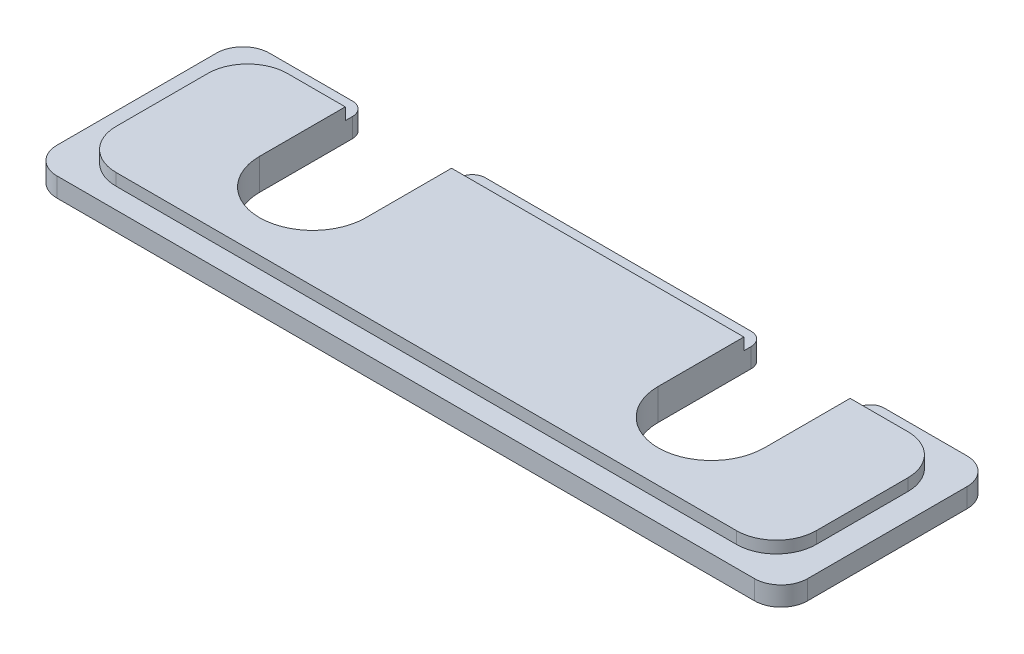
SolidWorks part; units mm, degrees
ref_plane "Front Plane" through (0, 0, 0) normal (0, 0, 1) x (1, 0, 0)
ref_plane "Top Plane" through (0, 0, 0) normal (0, 1, 0) x (1, 0, 0)
ref_plane "Right Plane" through (0, 0, 0) normal (1, 0, 0) x (0, 0, -1)
sketch "Sketch1" plane through (0, 0, 0) normal (0, 1, 0) x (1, 0, 0)
  line L1 (-26.25, -8) -> (26.25, -8)
  line L2 (-28.25, -6) -> (-28.25, 6)
  line L3 (-26.25, 8) -> (26.25, 8)
  line L4 (28.25, -6) -> (28.25, 6)
  line L5 (-28.25, -8) -> (28.25, 8) construction
  line L6 (-28.25, 8) -> (28.25, -8) construction
  arc A0 (26.25, 8) -> (28.25, 6) centre (26.25, 6) cw
  arc A1 (26.25, -8) -> (28.25, -6) centre (26.25, -6) ccw
  arc A2 (-26.25, -8) -> (-28.25, -6) centre (-26.25, -6) cw
  arc A3 (-28.25, 6) -> (-26.25, 8) centre (-26.25, 6) cw
  point P0 (0, 0)
  dimension "D3" = 2
  dimension "D1" = 56.5
  dimension "D2" = 16
extrude "Boss-Extrude1" add sketch "Sketch1" along normal blind 1.45
sketch "Sketch2" plane through (0, 1.45, 0) normal (0, 1, 0) x (1, 0, 0)
  line L1 (-23.35, -6.45) -> (23.35, -6.45)
  line L2 (-26.35, -3.45) -> (-26.35, 3.45)
  line L3 (-23.35, 6.45) -> (23.35, 6.45)
  line L4 (26.35, -3.45) -> (26.35, 3.45)
  line L5 (-26.35, -6.45) -> (26.35, 6.45) construction
  line L6 (-26.35, 6.45) -> (26.35, -6.45) construction
  arc A0 (23.35, -6.45) -> (26.35, -3.45) centre (23.35, -3.45) ccw
  arc A1 (23.35, 6.45) -> (26.35, 3.45) centre (23.35, 3.45) cw
  arc A2 (-23.35, -6.45) -> (-26.35, -3.45) centre (-23.35, -3.45) cw
  arc A3 (-26.35, 3.45) -> (-23.35, 6.45) centre (-23.35, 3.45) cw
  point P0 (0, 0)
  dimension "D3" = 3
  dimension "D1" = 52.7
  dimension "D2" = 12.9
extrude "Boss-Extrude2" add sketch "Sketch2" along normal blind 0.9
sketch "Sketch3" plane through (0, 2.35, 0) normal (0, 1, 0) x (1, 0, 0)
  line L0 (-19, 0) -> (-19, 8)
  line L1 (-19, 8) -> (-11, 8)
  line L2 (-11, 8) -> (-11, 0)
  line L3 (11, 0) -> (11, 8)
  line L4 (11, 8) -> (19, 8)
  line L5 (19, 8) -> (19, 0)
  line L6 (26.25, 8) -> (-26.25, 8) construction
  arc A0 (-19, 0) -> (-11, 0) centre (-15, 0) ccw
  arc A1 (11, 0) -> (19, 0) centre (15, 0) ccw
  dimension "D1" = 8
  dimension "D2" = 15
  dimension "D3" = 15
extrude "Cut-Extrude1" cut sketch "Sketch3" against normal through all
fillet "Fillet1" radius 1 4 edges at (19, 0.725, -8) (11, 0.725, -8) (-11, 0.725, -8) (-19, 0.725, -8)
